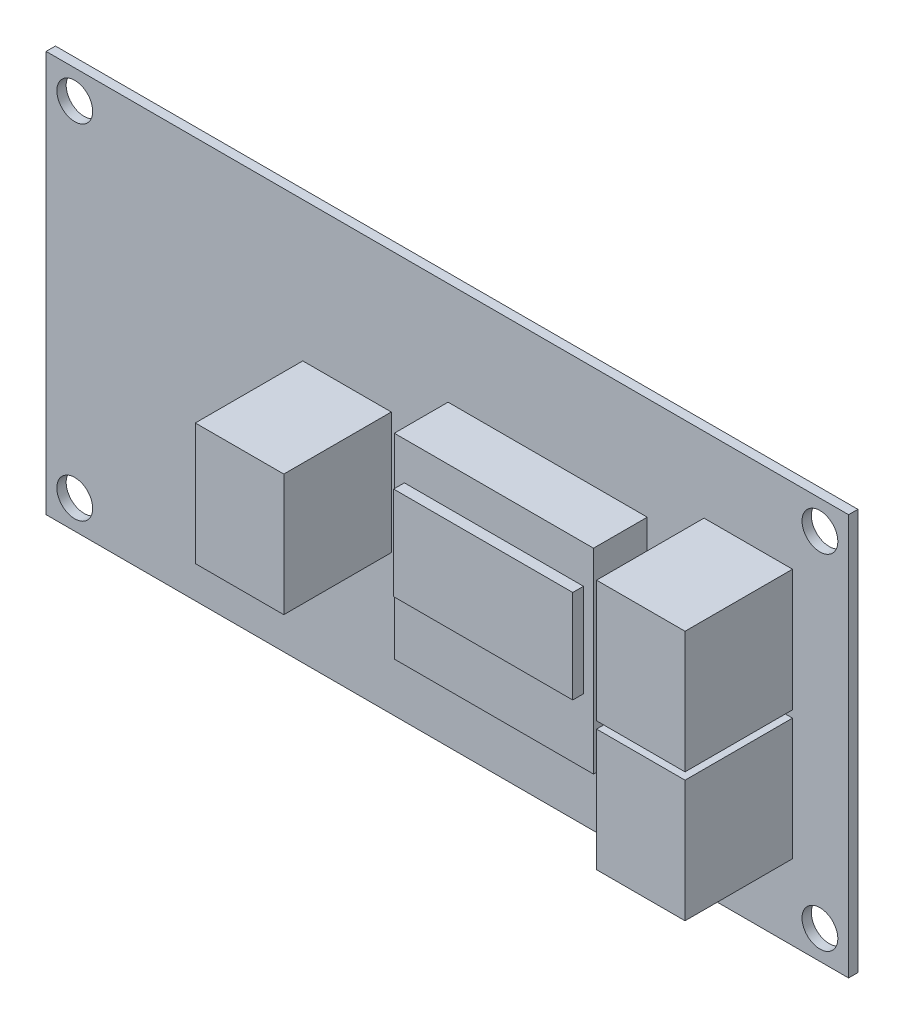
SolidWorks part; units mm, degrees
ref_plane "Front Plane" through (0, 0, 0) normal (0, 0, 1) x (1, 0, 0)
ref_plane "Top Plane" through (0, 0, 0) normal (0, 1, 0) x (1, 0, 0)
ref_plane "Right Plane" through (0, 0, 0) normal (1, 0, 0) x (0, 0, -1)
sketch "Sketch1" plane through (0, 0, 0) normal (0, 0, 1) x (1, 0, 0)
  line L1 (0, 0) -> (56, 0)
  line L2 (0, 0) -> (0, 56)
  line L3 (0, 56) -> (56, 56)
  line L4 (56, 0) -> (56, 56)
extrude "Boss-Extrude1" add sketch "Sketch1" along normal blind 1.3
sketch "Sketch2" plane through (0, 0, 1.3) normal (0, 0, 1) x (1, 0, 0)
  line L0 (56, 56) -> (28, 56)
  line L1 (56, 56) -> (0, 56) construction
  line L2 (42, 56) -> (42, 28)
  line L3 (42, 28.5) -> (42, 45.5)
  line L4 (0.1, 41.65) -> (0.1, 14.35)
  line L5 (42, 45.5) -> (35.825, 45.5)
  line L6 (35.825, 45.5) -> (35.825, 28.5)
  line L7 (42, 28) -> (42, 28.5)
  line L8 (35.825, 28.5) -> (48.175, 28.5)
  line L9 (48.175, 28.5) -> (48.175, 45.5)
  line L10 (48.175, 45.5) -> (42, 45.5)
  line L11 (28, 56) -> (0, 56)
  line L12 (48.175, 10.5) -> (42, 10.5)
  line L13 (48.175, 27.5) -> (48.175, 10.5)
  line L14 (35.825, 27.5) -> (48.175, 27.5)
  line L15 (35.825, 10.5) -> (35.825, 27.5)
  line L16 (42, 10.5) -> (35.825, 10.5)
  line L17 (42, 27.5) -> (42, 10.5)
  line L18 (14, 56) -> (14, 0)
  line L19 (0, 0) -> (56, 0) construction
  line L20 (14, 28) -> (14, 41.65)
  line L21 (14, 41.65) -> (0.1, 41.65)
  line L22 (0.1, 14.35) -> (27.9, 14.35)
  line L23 (27.9, 14.35) -> (27.9, 41.65)
  line L24 (27.9, 41.65) -> (14, 41.65)
extrude "Boss-Extrude2" add sketch "Sketch2" along normal blind 7.5 contours L4 L22 L18 L21 | L23 L24 L18 L22 | L6 L8 L2 L5 | L9 L10 L2 L8 | L14 L17 L12 L13 | L17 L14 L15 L16
sketch "Sketch3" plane through (0, 0, 8.8) normal (0, 0, 1) x (1, 0, 0)
  line L1 (35.825, 45.5) -> (48.175, 45.5)
  line L2 (35.825, 45.5) -> (35.825, 28.5)
  line L3 (35.825, 28.5) -> (48.175, 28.5)
  line L4 (48.175, 45.5) -> (48.175, 28.5)
  line L5 (35.825, 27.5) -> (48.175, 27.5)
  line L6 (35.825, 27.5) -> (35.825, 10.5)
  line L7 (35.825, 10.5) -> (48.175, 10.5)
  line L8 (48.175, 27.5) -> (48.175, 10.5)
extrude "Boss-Extrude3" add sketch "Sketch3" along normal blind 7.5
sketch "Sketch4" plane through (0, 0, 8.8) normal (0, 0, 1) x (1, 0, 0)
  line L0 (14, 14.35) -> (14, 23.35)
  line L1 (0.1, 14.35) -> (27.9, 14.35) construction
  line L2 (14, 23.35) -> (1.5, 23.35)
  line L3 (1.5, 23.35) -> (1.5, 36.35)
  line L4 (1.5, 36.35) -> (26.5, 36.35)
  line L5 (26.5, 36.35) -> (26.5, 23.35)
  line L6 (26.5, 23.35) -> (14, 23.35)
extrude "Boss-Extrude4" add sketch "Sketch4" along normal blind 1.5 contours L6 L5 L4 L3 L2
sketch "Sketch5" plane through (0, 0, 1.3) normal (0, 0, 1) x (1, 0, 0)
  line L1 (0, 56) -> (-56, 56)
  line L2 (0, 56) -> (0, 0)
  line L3 (0, 0) -> (-56, 0)
  line L4 (-56, 56) -> (-56, 0)
extrude "Boss-Extrude5" add sketch "Sketch5" against normal blind 1.3
sketch "Sketch7" plane through (0, 0, 1.3) normal (0, 0, 1) x (1, 0, 0)
  line L0 (0, 56) -> (0, 0)
  line L1 (56, 56) -> (-56, 56) construction
  line L2 (-56, 0) -> (56, 0) construction
  line L3 (0, 0) -> (0, 28)
  line L4 (0, 28) -> (-56, 28)
  line L5 (-56, 56) -> (-56, 0) construction
  line L6 (-56, 56) -> (-52, 56)
  line L7 (-52, 56) -> (-52, 52)
  line L8 (52, 56) -> (52, 52)
  line L9 (56, 56) -> (52, 56)
  circle A0 centre (-52, 52) radius 2.5
  circle A1 centre (-52, 4) radius 2.5
  circle A2 centre (52, 4) radius 2.5
  circle A3 centre (52, 52) radius 2.5
extrude "Cut-Extrude1" cut sketch "Sketch7" against normal blind 1.3
sketch "Sketch8" plane through (0, 0, 1.3) normal (0, 0, 1) x (1, 0, 0)
  line L0 (56, 56) -> (0, 56)
  line L1 (56, 56) -> (-56, 56) construction
  line L2 (0, 56) -> (-14, 56)
  line L3 (-14, 56) -> (-14, 0)
  line L4 (-56, 0) -> (56, 0) construction
  line L5 (-14, 28) -> (-20.175, 28)
  line L6 (-20.175, 28) -> (-20.175, 36.5)
  line L7 (-20.175, 36.5) -> (-7.825, 36.5)
  line L8 (-7.825, 36.5) -> (-7.825, 19.5)
  line L9 (-7.825, 19.5) -> (-20.175, 19.5)
  line L10 (-20.175, 19.5) -> (-20.175, 28)
extrude "Boss-Extrude6" add sketch "Sketch8" along normal blind 15 contours L9 L8 L7 L3 | L7 L6 L5 L3 | L10 L9 L3 L5
